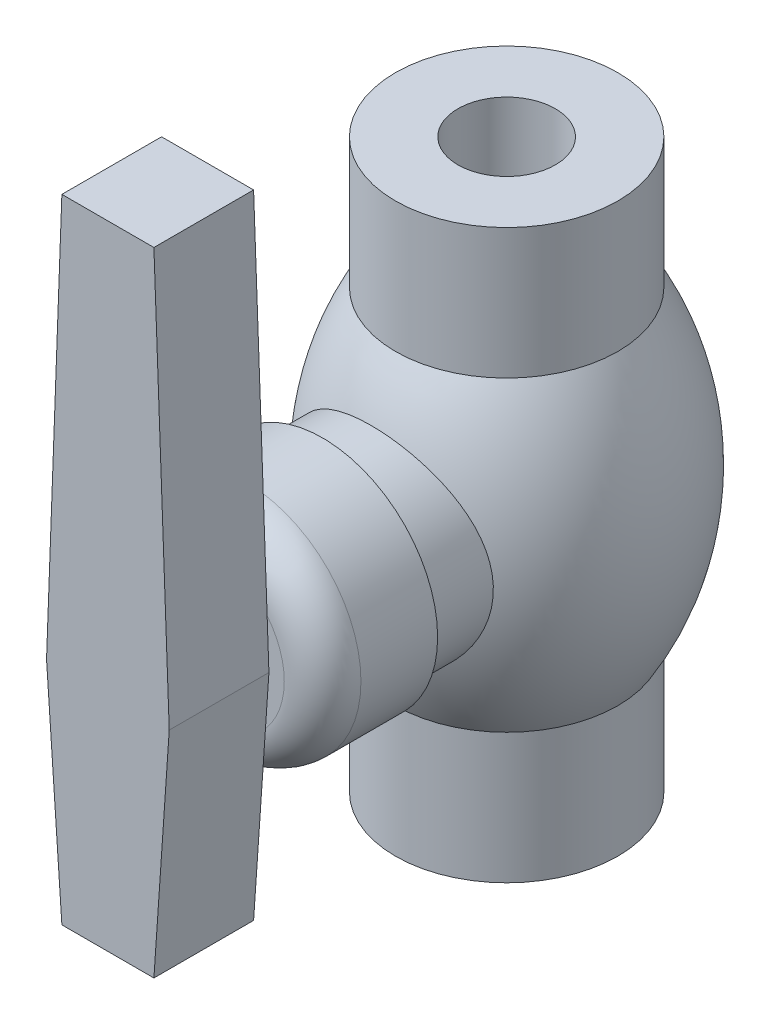
SolidWorks part; units mm, degrees
ref_plane "Alzado" through (0, 0, 0) normal (0, 0, 1) x (1, 0, 0)
ref_plane "Planta" through (0, 0, 0) normal (0, 1, 0) x (1, 0, 0)
ref_plane "Vista lateral" through (0, 0, 0) normal (1, 0, 0) x (0, 0, -1)
sketch "Croquis1" plane through (0, 0, 0) normal (0, 0, 1) x (1, 0, 0)
  line L0 (0, 0) -> (14.5, 0)
  line L1 (14.5, 0) -> (14.5, 17)
  line L2 (14.5, 57) -> (14.5, 74)
  line L3 (20, 74) -> (20, -1.2648) construction
  line L4 (14.5, 74) -> (0, 74)
  line L5 (0, 74) -> (0, 0)
  arc A0 (14.5, 57) -> (14.5, 17) centre (-19.1136, 37) cw
  dimension "D1" = 14.5
  dimension "D2" = 17
  dimension "D3" = 17
  dimension "D4" = 40
  dimension "D5" = 20
revolve "Revolución1" add sketch "Croquis1" angle 360 about L5
sketch "Croquis2" plane through (0, 74, 0) normal (0, 1, 0) x (1, 0, 0)
  circle A0 centre (0, 0) radius 6.35
  dimension "D1" = 12.7
extrude "Cortar-Extruir1" cut sketch "Croquis2" against normal through all
sketch "Croquis3" plane through (0, 0, 0) normal (0, 0, 1) x (1, 0, 0)
  line L0 (-20, 37) -> (20, 37) construction
  arc A0 (-14.5, 57) -> (-14.5, 17) centre (19.1136, 37) ccw construction
  arc A1 (14.5, 17) -> (14.5, 57) centre (-19.1136, 37) ccw construction
  circle A2 centre (0, 37) radius 13.25
  dimension "D1" = 26.5
extrude "Saliente-Extruir1" add sketch "Croquis3" along normal blind 24
sketch "Croquis4" plane through (0, 74, 0) normal (0, 1, 0) x (1, 0, 0)
  circle A0 centre (0, 0) radius 6.35
extrude "Cortar-Extruir2" cut sketch "Croquis4" against normal through all
sketch "Croquis5" plane through (0, 0, 24) normal (0, 0, 1) x (1, 0, 0)
  circle A0 centre (0, 37) radius 15
  dimension "D1" = 30
extrude "Saliente-Extruir2" add sketch "Croquis5" along normal blind 15
fillet "Redondeo1" radius 5 1 edges at (15, 37, 39)
sketch "Croquis7" plane through (0, 0, 39) normal (0, 0, 1) x (1, 0, 0)
  line L3 (0, 37) -> (0, 90.5) construction
  line L4 (-6, 90.5) -> (6, 90.5)
  line L5 (0, 37) -> (0, -14.1315) construction
  line L6 (-6, 8) -> (6, 8)
  line L7 (-8, 37) -> (-6, 90.5)
  line L8 (6, 90.5) -> (8, 37)
  line L10 (-6, 8) -> (-8, 37)
  line L11 (8, 37) -> (6, 8)
  point P9 (0, 90.5)
  point P13 (0, 8)
  dimension "D1" = 8
  dimension "D2" = 8
  dimension "D3" = 12
  dimension "D4" = 12
  dimension "D5" = 29
  dimension "D6" = 82.5
extrude "Saliente-Extruir3" add sketch "Croquis7" along normal blind 13
